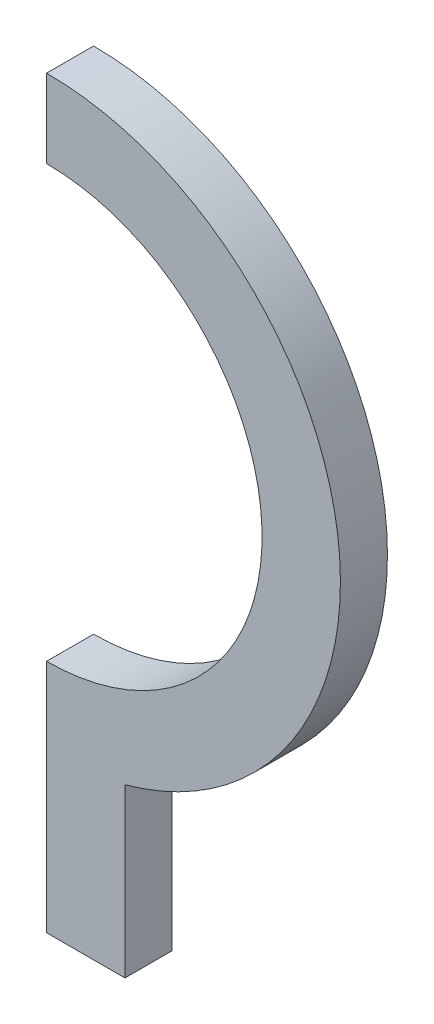
SolidWorks part; units mm, degrees
material "Balsa"
ref_plane "Front Plane" through (0, 0, 0) normal (1, 0, 0) x (0, 1, 0)
ref_plane "Top Plane" through (0, 0, 0) normal (0, 0, 1) x (0, 1, 0)
ref_plane "Right Plane" through (0, 0, 0) normal (0, 1, 0) x (-1, 0, 0)
sketch "Sketch1" plane through (0, 0, 0) normal (0, 0, 1) x (0, 1, 0)
  line L0 (10, 5) -> (20, 5)
  line L1 (10, -5) -> (-10, -5)
  line L3 (10, 5) -> (-10, 5)
  line L4 (-10, -5) -> (-10, 5)
  line L5 (10, -5) -> (-10, 5) construction
  line L6 (10, 5) -> (-10, -5) construction
  line L7 (10, -5) -> (11.3579, -5)
  line L8 (75, 5) -> (85, 5)
  arc A0 (20, 5) -> (75, 5) centre (47.5, 5) ccw
  arc A1 (11.3579, -5) -> (85, 5) centre (47.5, 5) ccw
  circle A3 centre (47.5, 5) radius 27.5 construction
  circle A4 centre (47.5, 5) radius 37.5 construction
  point P0 (0, 0)
  point P7 (108.3614, 15.9639)
  point P10 (98.7984, 13.0402)
  dimension "D3" = 55
  dimension "D5" = 37.5
  dimension "D6" = 10
  dimension "D1" = 10
  dimension "D2" = 20
  dimension "D4" = 10
extrude "Boss-Extrude1" add sketch "Sketch1" along normal blind 6
